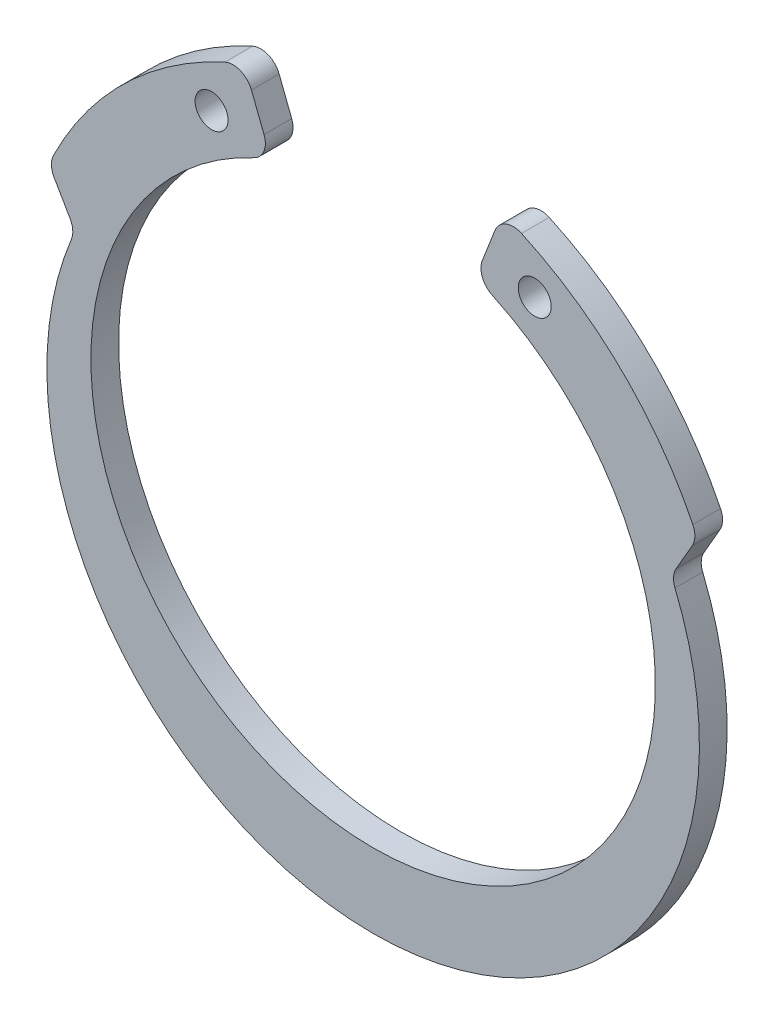
SolidWorks part; units mm, degrees
material "AISI 316 Annealed Stainless Steel Bar (SS)"
ref_plane "Front Plane" through (0, 0, 0) normal (0, 0, 1) x (1, 0, 0)
ref_plane "Top Plane" through (0, 0, 0) normal (0, 1, 0) x (1, 0, 0)
ref_plane "Right Plane" through (0, 0, 0) normal (1, 0, 0) x (0, 0, -1)
sketch "Sketch1" plane through (0, 0, 0) normal (0, 0, 1) x (1, 0, 0)
  line L0 (0, 21.843) -> (0, -18.1651) construction
  line L1 (0, -10.8712) -> (0, -13.7287)
  line L2 (12.49, 5.6989) -> (11.4805, 3.9504)
  line L3 (4.9718, 12.7968) -> (3.937, 10.1333)
  line L4 (6.9459, 11.842) -> (6.223, 10.6096) construction
  line L5 (6.223, 10.6096) -> (5.5001, 9.3772) construction
  arc A0 (0, -10.8712) -> (3.937, 10.1333) centre (0, 0) ccw
  arc A1 (12.49, 5.6989) -> (4.9718, 12.7968) centre (0, 0) ccw
  arc A2 (0, -13.7287) -> (11.4805, 3.9504) centre (0, -1.1615) ccw
  circle A3 centre (6.223, 10.6096) radius 0.635
  dimension "D1" = 21.7424
  dimension "D2" = 27.4574
  dimension "D3" = 7.874
  dimension "D7" = 1.27
  dimension "D4" = 9.7536
  dimension "D5" = 30
  dimension "D6" = 1.27
  dimension "D8" = 12.446
extrude "Boss-Extrude1" add sketch "Sketch1" along normal mid plane 1.0668
fillet "Fillet1" radius 0.762 4 edges at (3.937, 10.1333, 0) (4.9718, 12.7968, 0) (11.4805, 3.9504, 0) (12.49, 5.6989, 0)
mirror "Mirror1" about plane through (0, 0, 0) normal (1, 0, 0) of bodies 101
